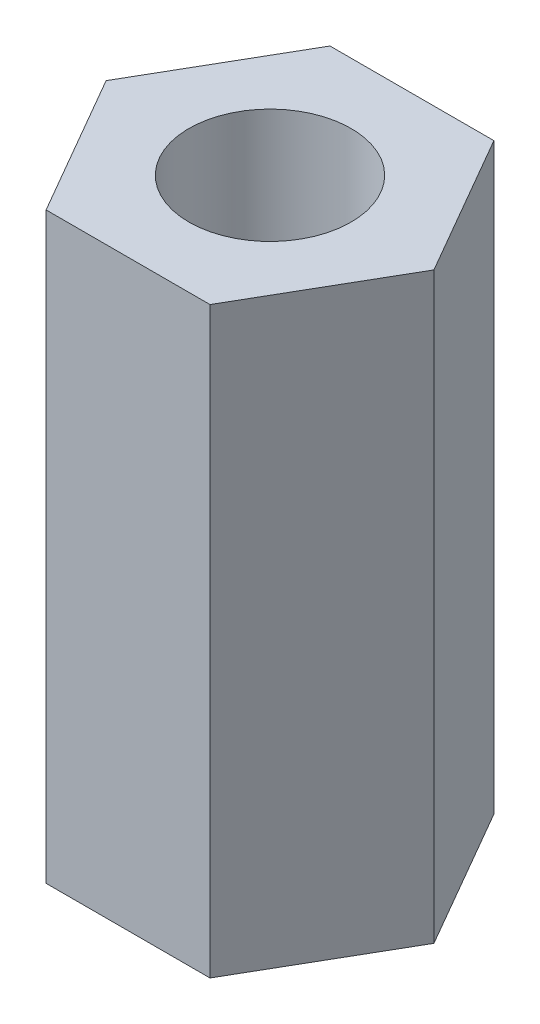
SolidWorks part; units mm, degrees
ref_plane "Front Plane" through (0, 0, 0) normal (0, 0, 1) x (1, 0, 0)
ref_plane "Top Plane" through (0, 0, 0) normal (0, 1, 0) x (1, 0, 0)
ref_plane "Right Plane" through (0, 0, 0) normal (1, 0, 0) x (0, 0, -1)
sketch "Sketch1" plane through (0, 0, 0) normal (0, 1, 0) x (1, 0, 0)
  line L1 (2.0207, 3.5) -> (-2.0207, 3.5)
  line L2 (-2.0207, 3.5) -> (-4.0415, 0)
  line L3 (-4.0415, 0) -> (-2.0207, -3.5)
  line L4 (-2.0207, -3.5) -> (2.0207, -3.5)
  line L5 (2.0207, -3.5) -> (4.0415, 0)
  line L6 (4.0415, 0) -> (2.0207, 3.5)
  circle A0 centre (0, 0) radius 3.5 construction
  circle A1 centre (0, 0) radius 2
  dimension "D1" = 4
  dimension "D2" = 7
extrude "Boss-Extrude1" add sketch "Sketch1" along normal blind 14.38
